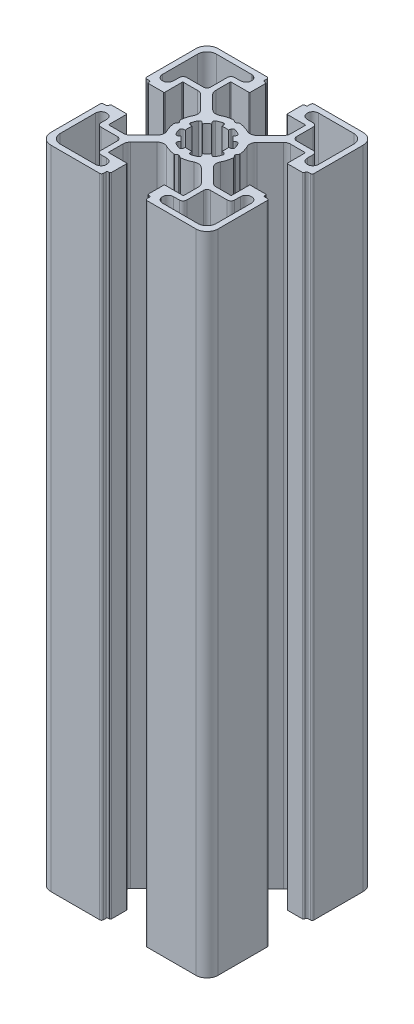
SolidWorks part; units mm, degrees
ref_plane "Front Plane" through (0, 0, 0) normal (0, 0, 1) x (1, 0, 0)
ref_plane "Top Plane" through (0, 0, 0) normal (0, 1, 0) x (1, 0, 0)
ref_plane "Right Plane" through (0, 0, 0) normal (1, 0, 0) x (0, 0, -1)
sketch "Sketch1" plane through (0, 0, 0) normal (0, 1, 0) x (1, 0, 0)
  line L106 (-18, 9.0002) -> (-18, 10.55)
  line L107 (-21, 18.5) -> (-21, 9.0002)
  line L108 (-9, 21) -> (-18.5, 21)
  line L109 (-10.55, 18) -> (-9, 18)
  line L110 (0.9675, 5.4811) -> (0.8674, 4.9242)
  line L111 (2.864, 4.0985) -> (3.1913, 4.5626)
  line L112 (4.5668, 3.2081) -> (4.0897, 2.8765)
  line L113 (4.9205, 0.8878) -> (5.4897, 0.9862)
  line L114 (5.4898, -0.9862) -> (4.9205, -0.8878)
  line L115 (4.0897, -2.8765) -> (4.5668, -3.2082)
  line L116 (3.1914, -4.5627) -> (2.864, -4.0985)
  line L117 (0.8674, -4.9242) -> (0.9675, -5.4811)
  line L118 (-0.9675, -5.4811) -> (-0.8674, -4.9242)
  line L119 (-2.864, -4.0985) -> (-3.1913, -4.5626)
  line L120 (-4.5668, -3.2082) -> (-4.0897, -2.8765)
  line L121 (-4.9205, -0.8878) -> (-5.4897, -0.9862)
  line L122 (-5.4899, 0.9862) -> (-4.9205, 0.8878)
  line L123 (-4.0897, 2.8765) -> (-4.5668, 3.2081)
  line L124 (-3.1914, 4.5627) -> (-2.864, 4.0985)
  line L125 (-0.8674, 4.9242) -> (-0.9675, 5.4811)
  line L126 (-11.55, 12.55) -> (-11.55, 17)
  line L127 (-17, 11.55) -> (-12.55, 11.55)
  line L128 (-21, -9.0002) -> (-21, -18.5)
  line L129 (-18, -10.55) -> (-18, -9.0002)
  line L130 (-12.55, -11.55) -> (-17, -11.55)
  line L131 (-11.55, -17) -> (-11.55, -12.55)
  line L132 (-9, -18) -> (-10.55, -18)
  line L133 (-18.5, -21) -> (-9, -21)
  line L134 (21, 9.0002) -> (21, 18.5)
  line L135 (18, 10.55) -> (18, 9.0002)
  line L136 (12.55, 11.55) -> (17, 11.55)
  line L137 (11.55, 17) -> (11.55, 12.55)
  line L138 (9, 18) -> (10.55, 18)
  line L139 (18.5, 21) -> (9, 21)
  line L140 (17, -11.55) -> (12.55, -11.55)
  line L141 (18, -9.0002) -> (18, -10.55)
  line L142 (21, -18.5) -> (21, -9.0002)
  line L143 (9, -21) -> (18.5, -21)
  line L144 (10.55, -18) -> (9, -18)
  line L145 (11.55, -12.55) -> (11.55, -17)
  line L146 (7.5635, 5.8587) -> (11.1298, 9.425)
  line L147 (12.5048, 9.9945) -> (16.3169, 9.9945)
  line L148 (16.5169, 9.7945) -> (16.5169, 5.2)
  line L149 (16.7169, 5) -> (20.7196, 5)
  line L150 (21.0196, 5.3) -> (21.0196, 5.5)
  line L151 (21.3196, 5.8) -> (22, 5.8)
  line L152 (22.5, 6.3) -> (22.5, 19.5)
  line L153 (19.5, 22.5) -> (6.3757, 22.5)
  line L154 (5.8757, 22) -> (5.8757, 21.3)
  line L155 (5.5757, 21) -> (5.3, 21)
  line L156 (5, 20.7) -> (5, 16.6668)
  line L157 (5.2, 16.4668) -> (9.9054, 16.4668)
  line L158 (10.1054, 16.2668) -> (10.1054, 12.4716)
  line L159 (9.5196, 11.0574) -> (5.9449, 7.4827)
  line L160 (0.7548, 7.9748) -> (0.1126, 7.6069)
  line L161 (-0.1126, 7.6069) -> (-0.7547, 7.9748)
  line L162 (-5.9449, 7.4827) -> (-9.5196, 11.0574)
  line L163 (-10.1054, 12.4716) -> (-10.1054, 16.2668)
  line L164 (-9.9054, 16.4668) -> (-5.2, 16.4668)
  line L165 (-5, 16.6668) -> (-5, 20.7)
  line L166 (-5.3, 21) -> (-5.5757, 21)
  line L167 (-5.8757, 21.3) -> (-5.8757, 22)
  line L168 (-6.3757, 22.5) -> (-19.5, 22.5)
  line L169 (-22.5, 19.5) -> (-22.5, 6.3)
  line L170 (-22, 5.8) -> (-21.3196, 5.8)
  line L171 (-21.0196, 5.5) -> (-21.0196, 5.3)
  line L172 (-20.7196, 5) -> (-16.7169, 5)
  line L173 (-16.5169, 5.2) -> (-16.5169, 9.7945)
  line L174 (-16.3169, 9.9945) -> (-12.5048, 9.9945)
  line L175 (-11.1298, 9.425) -> (-7.5635, 5.8587)
  line L176 (-7.974, 0.7926) -> (-7.5401, 0.0468)
  line L177 (-7.5401, -0.0468) -> (-7.974, -0.7926)
  line L178 (-7.5635, -5.8587) -> (-11.1298, -9.425)
  line L179 (-12.5048, -9.9945) -> (-16.3169, -9.9945)
  line L180 (-16.5169, -9.7945) -> (-16.5169, -5.2)
  line L181 (-16.7169, -5) -> (-20.7196, -5)
  line L182 (-21.0196, -5.3) -> (-21.0196, -5.5)
  line L183 (-21.3196, -5.8) -> (-22, -5.8)
  line L184 (-22.5, -6.3) -> (-22.5, -19.5)
  line L185 (-19.5, -22.5) -> (-6.3757, -22.5)
  line L186 (-5.8757, -22) -> (-5.8757, -21.3)
  line L187 (-5.5757, -21) -> (-5.3, -21)
  line L188 (-5, -20.7) -> (-5, -16.6668)
  line L189 (-5.2, -16.4668) -> (-9.9054, -16.4668)
  line L190 (-10.1054, -16.2668) -> (-10.1054, -12.4716)
  line L191 (-9.5196, -11.0574) -> (-5.9449, -7.4827)
  line L192 (-0.7547, -7.9748) -> (-0.1126, -7.6069)
  line L193 (0.1126, -7.6069) -> (0.7548, -7.9748)
  line L194 (5.9449, -7.4827) -> (9.5196, -11.0574)
  line L195 (10.1054, -12.4716) -> (10.1054, -16.2668)
  line L196 (9.9054, -16.4668) -> (5.2, -16.4668)
  line L197 (5, -16.6668) -> (5, -20.7)
  line L198 (5.3, -21) -> (5.5757, -21)
  line L199 (5.8757, -21.3) -> (5.8757, -22)
  line L200 (6.3757, -22.5) -> (19.5, -22.5)
  line L201 (22.5, -19.5) -> (22.5, -6.3)
  line L202 (22, -5.8) -> (21.3196, -5.8)
  line L203 (21.0196, -5.5) -> (21.0196, -5.3)
  line L204 (20.7196, -5) -> (16.7169, -5)
  line L205 (16.5169, -5.2) -> (16.5169, -9.7945)
  line L206 (16.3169, -9.9945) -> (12.5048, -9.9945)
  line L207 (11.1298, -9.425) -> (7.5635, -5.8587)
  line L208 (7.974, -0.7926) -> (7.5401, -0.0468)
  line L209 (7.5401, 0.0468) -> (7.974, 0.7926)
  arc A140 (-17, 11.55) -> (-18, 10.55) centre (-17, 10.55) ccw
  arc A141 (-21, 9.0002) -> (-18, 9.0002) centre (-19.5, 9.0002) ccw
  arc A142 (-18.5, 21) -> (-21, 18.5) centre (-18.5, 18.5) ccw
  arc A143 (-9, 18) -> (-9, 21) centre (-9, 19.5) ccw
  arc A144 (-10.55, 18) -> (-11.55, 17) centre (-10.55, 17) ccw
  arc A145 (-12.55, 11.55) -> (-11.55, 12.55) centre (-12.55, 12.55) ccw
  arc A146 (-21, -18.5) -> (-18.5, -21) centre (-18.5, -18.5) ccw
  arc A147 (-18, -9.0002) -> (-21, -9.0002) centre (-19.5, -9.0002) ccw
  arc A148 (-18, -10.55) -> (-17, -11.55) centre (-17, -10.55) ccw
  arc A149 (-11.55, -12.55) -> (-12.55, -11.55) centre (-12.55, -12.55) ccw
  arc A150 (-11.55, -17) -> (-10.55, -18) centre (-10.55, -17) ccw
  arc A151 (-9, -21) -> (-9, -18) centre (-9, -19.5) ccw
  arc A152 (0.8674, 4.9242) -> (-0.8674, 4.9242) centre (0, 0) ccw
  arc A153 (1.5951, 5.8941) -> (0.9675, 5.4811) centre (1.4627, 5.4119) ccw
  arc A154 (3.0417, 5.301) -> (1.5951, 5.8941) centre (0.0235, 0) ccw
  arc A155 (3.1913, 4.5626) -> (3.0417, 5.301) centre (2.7943, 4.8665) ccw
  arc A156 (4.0897, 2.8765) -> (2.864, 4.0985) centre (0, 0) ccw
  arc A157 (5.3025, 3.0565) -> (4.5668, 3.2081) centre (4.868, 2.8091) ccw
  arc A158 (5.906, 1.6142) -> (5.3025, 3.0565) centre (0.0235, 0) ccw
  arc A159 (5.4897, 0.9862) -> (5.906, 1.6142) centre (5.4239, 1.4819) ccw
  arc A160 (4.9205, -0.8878) -> (4.9205, 0.8878) centre (0, 0) ccw
  arc A161 (5.906, -1.6142) -> (5.4898, -0.9862) centre (5.4239, -1.4819) ccw
  arc A162 (5.3025, -3.0564) -> (5.906, -1.6142) centre (0.0235, 0) ccw
  arc A163 (4.5668, -3.2082) -> (5.3025, -3.0564) centre (4.868, -2.8091) ccw
  arc A164 (2.864, -4.0985) -> (4.0897, -2.8765) centre (0, 0) ccw
  arc A165 (3.0416, -5.301) -> (3.1914, -4.5627) centre (2.7943, -4.8665) ccw
  arc A166 (1.5951, -5.8941) -> (3.0416, -5.301) centre (0.0235, 0) ccw
  arc A167 (0.9675, -5.4811) -> (1.5951, -5.8941) centre (1.4627, -5.4119) ccw
  arc A168 (-0.8674, -4.9242) -> (0.8674, -4.9242) centre (0, 0) ccw
  arc A169 (-1.5951, -5.8941) -> (-0.9675, -5.4811) centre (-1.4627, -5.4119) ccw
  arc A170 (-3.0416, -5.301) -> (-1.5951, -5.8941) centre (-0.0235, 0) ccw
  arc A171 (-3.1913, -4.5626) -> (-3.0416, -5.301) centre (-2.7943, -4.8665) ccw
  arc A172 (-4.0897, -2.8765) -> (-2.864, -4.0985) centre (0, 0) ccw
  arc A173 (-5.3025, -3.0565) -> (-4.5668, -3.2082) centre (-4.868, -2.8091) ccw
  arc A174 (-5.906, -1.6142) -> (-5.3025, -3.0565) centre (-0.0235, 0) ccw
  arc A175 (-5.4897, -0.9862) -> (-5.906, -1.6142) centre (-5.4239, -1.4819) ccw
  arc A176 (-4.9205, 0.8878) -> (-4.9205, -0.8878) centre (0, 0) ccw
  arc A177 (-5.906, 1.6141) -> (-5.4899, 0.9862) centre (-5.4239, 1.4818) ccw
  arc A178 (-5.3025, 3.0564) -> (-5.906, 1.6141) centre (-0.0235, 0) ccw
  arc A179 (-4.5668, 3.2081) -> (-5.3025, 3.0564) centre (-4.868, 2.8091) ccw
  arc A180 (-2.864, 4.0985) -> (-4.0897, 2.8765) centre (0, 0) ccw
  arc A181 (-3.0417, 5.301) -> (-3.1914, 4.5627) centre (-2.7943, 4.8665) ccw
  arc A182 (-1.5951, 5.8941) -> (-3.0417, 5.301) centre (-0.0235, 0) ccw
  arc A183 (-0.9675, 5.4811) -> (-1.5951, 5.8941) centre (-1.4627, 5.4119) ccw
  arc A184 (21, 18.5) -> (18.5, 21) centre (18.5, 18.5) ccw
  arc A185 (18, 9.0002) -> (21, 9.0002) centre (19.5, 9.0002) ccw
  arc A186 (18, 10.55) -> (17, 11.55) centre (17, 10.55) ccw
  arc A187 (11.55, 12.55) -> (12.55, 11.55) centre (12.55, 12.55) ccw
  arc A188 (11.55, 17) -> (10.55, 18) centre (10.55, 17) ccw
  arc A189 (9, 21) -> (9, 18) centre (9, 19.5) ccw
  arc A190 (12.55, -11.55) -> (11.55, -12.55) centre (12.55, -12.55) ccw
  arc A191 (17, -11.55) -> (18, -10.55) centre (17, -10.55) ccw
  arc A192 (21, -9.0002) -> (18, -9.0002) centre (19.5, -9.0002) ccw
  arc A193 (18.5, -21) -> (21, -18.5) centre (18.5, -18.5) ccw
  arc A194 (9, -18) -> (9, -21) centre (9, -19.5) ccw
  arc A195 (10.55, -18) -> (11.55, -17) centre (10.55, -17) ccw
  arc A196 (7.9999, 0.9154) -> (7.2004, 3.6119) centre (0.0496, 0.0249) ccw
  arc A197 (7.5635, 5.8587) -> (7.2004, 3.6119) centre (8.9385, 4.4837) ccw
  arc A198 (12.5048, 9.9945) -> (11.1298, 9.425) centre (12.5048, 8.05) ccw
  arc A199 (16.5169, 9.7945) -> (16.3169, 9.9945) centre (16.3169, 9.7945) ccw
  arc A200 (16.5169, 5.2) -> (16.7169, 5) centre (16.7169, 5.2) ccw
  arc A201 (20.7196, 5) -> (21.0196, 5.3) centre (20.7196, 5.3) ccw
  arc A202 (21.3196, 5.8) -> (21.0196, 5.5) centre (21.3196, 5.5) ccw
  arc A203 (22, 5.8) -> (22.5, 6.3) centre (22, 6.3) ccw
  arc A204 (22.5, 19.5) -> (19.5, 22.5) centre (19.5, 19.5) ccw
  arc A205 (6.3757, 22.5) -> (5.8757, 22) centre (6.3757, 22) ccw
  arc A206 (5.5757, 21) -> (5.8757, 21.3) centre (5.5757, 21.3) ccw
  arc A207 (5.3, 21) -> (5, 20.7) centre (5.3, 20.7) ccw
  arc A208 (5, 16.6668) -> (5.2, 16.4668) centre (5.2, 16.6668) ccw
  arc A209 (10.1054, 16.2668) -> (9.9054, 16.4668) centre (9.9054, 16.2668) ccw
  arc A210 (9.5196, 11.0574) -> (10.1054, 12.4716) centre (8.1054, 12.4716) ccw
  arc A211 (3.6665, 7.1733) -> (5.9449, 7.4827) centre (4.5855, 8.9496) ccw
  arc A212 (3.6665, 7.1733) -> (0.8753, 8.0001) centre (0.0235, 0) ccw
  arc A213 (0.8753, 8.0001) -> (0.7548, 7.9748) centre (0.8542, 7.8013) ccw
  arc A214 (0, 7.531) -> (0.1126, 7.6069) centre (-0.0489, 7.7249) ccw
  arc A215 (-0.1126, 7.6069) -> (0, 7.531) centre (0.0489, 7.7249) ccw
  arc A216 (-0.7547, 7.9748) -> (-0.8753, 8.0001) centre (-0.8542, 7.8013) ccw
  arc A217 (-0.8753, 8.0001) -> (-3.6665, 7.1733) centre (-0.0235, 0) ccw
  arc A218 (-5.9449, 7.4827) -> (-3.6665, 7.1733) centre (-4.5855, 8.9496) ccw
  arc A219 (-10.1054, 12.4716) -> (-9.5196, 11.0574) centre (-8.1054, 12.4716) ccw
  arc A220 (-9.9054, 16.4668) -> (-10.1054, 16.2668) centre (-9.9054, 16.2668) ccw
  arc A221 (-5.2, 16.4668) -> (-5, 16.6668) centre (-5.2, 16.6668) ccw
  arc A222 (-5, 20.7) -> (-5.3, 21) centre (-5.3, 20.7) ccw
  arc A223 (-5.8757, 21.3) -> (-5.5757, 21) centre (-5.5757, 21.3) ccw
  arc A224 (-5.8757, 22) -> (-6.3757, 22.5) centre (-6.3757, 22) ccw
  arc A225 (-19.5, 22.5) -> (-22.5, 19.5) centre (-19.5, 19.5) ccw
  arc A226 (-22.5, 6.3) -> (-22, 5.8) centre (-22, 6.3) ccw
  arc A227 (-21.0196, 5.5) -> (-21.3196, 5.8) centre (-21.3196, 5.5) ccw
  arc A228 (-21.0196, 5.3) -> (-20.7196, 5) centre (-20.7196, 5.3) ccw
  arc A229 (-16.7169, 5) -> (-16.5169, 5.2) centre (-16.7169, 5.2) ccw
  arc A230 (-16.3169, 9.9945) -> (-16.5169, 9.7945) centre (-16.3169, 9.7945) ccw
  arc A231 (-11.1298, 9.425) -> (-12.5048, 9.9945) centre (-12.5048, 8.05) ccw
  arc A232 (-7.2004, 3.6119) -> (-7.5635, 5.8587) centre (-8.9385, 4.4837) ccw
  arc A233 (-7.2004, 3.6119) -> (-7.9999, 0.9154) centre (-0.0496, 0.0249) ccw
  arc A234 (-7.9999, 0.9154) -> (-7.974, 0.7926) centre (-7.8011, 0.8932) ccw
  arc A235 (-7.5313, 0) -> (-7.5401, 0.0468) centre (-7.7309, -0.013) ccw
  arc A236 (-7.5401, -0.0468) -> (-7.5313, 0) centre (-7.7309, 0.013) ccw
  arc A237 (-7.974, -0.7926) -> (-7.9999, -0.9154) centre (-7.8011, -0.8932) ccw
  arc A238 (-7.9999, -0.9154) -> (-7.2004, -3.6119) centre (-0.0496, -0.0249) ccw
  arc A239 (-7.5635, -5.8587) -> (-7.2004, -3.6119) centre (-8.9385, -4.4837) ccw
  arc A240 (-12.5048, -9.9945) -> (-11.1298, -9.425) centre (-12.5048, -8.05) ccw
  arc A241 (-16.5169, -9.7945) -> (-16.3169, -9.9945) centre (-16.3169, -9.7945) ccw
  arc A242 (-16.5169, -5.2) -> (-16.7169, -5) centre (-16.7169, -5.2) ccw
  arc A243 (-20.7196, -5) -> (-21.0196, -5.3) centre (-20.7196, -5.3) ccw
  arc A244 (-21.3196, -5.8) -> (-21.0196, -5.5) centre (-21.3196, -5.5) ccw
  arc A245 (-22, -5.8) -> (-22.5, -6.3) centre (-22, -6.3) ccw
  arc A246 (-22.5, -19.5) -> (-19.5, -22.5) centre (-19.5, -19.5) ccw
  arc A247 (-6.3757, -22.5) -> (-5.8757, -22) centre (-6.3757, -22) ccw
  arc A248 (-5.5757, -21) -> (-5.8757, -21.3) centre (-5.5757, -21.3) ccw
  arc A249 (-5.3, -21) -> (-5, -20.7) centre (-5.3, -20.7) ccw
  arc A250 (-5, -16.6668) -> (-5.2, -16.4668) centre (-5.2, -16.6668) ccw
  arc A251 (-10.1054, -16.2668) -> (-9.9054, -16.4668) centre (-9.9054, -16.2668) ccw
  arc A252 (-9.5196, -11.0574) -> (-10.1054, -12.4716) centre (-8.1054, -12.4716) ccw
  arc A253 (-3.6665, -7.1733) -> (-5.9449, -7.4827) centre (-4.5855, -8.9496) ccw
  arc A254 (-3.6665, -7.1733) -> (-0.8753, -8.0001) centre (-0.0235, 0) ccw
  arc A255 (-0.8753, -8.0001) -> (-0.7547, -7.9748) centre (-0.8542, -7.8013) ccw
  arc A256 (0, -7.531) -> (-0.1126, -7.6069) centre (0.0489, -7.7249) ccw
  arc A257 (0.1126, -7.6069) -> (0, -7.531) centre (-0.0489, -7.7249) ccw
  arc A258 (0.7548, -7.9748) -> (0.8753, -8.0001) centre (0.8542, -7.8012) ccw
  arc A259 (0.8753, -8.0001) -> (3.6665, -7.1733) centre (0.0235, 0) ccw
  arc A260 (5.9449, -7.4827) -> (3.6665, -7.1733) centre (4.5855, -8.9496) ccw
  arc A261 (10.1054, -12.4716) -> (9.5196, -11.0574) centre (8.1054, -12.4716) ccw
  arc A262 (9.9054, -16.4668) -> (10.1054, -16.2668) centre (9.9054, -16.2668) ccw
  arc A263 (5.2, -16.4668) -> (5, -16.6668) centre (5.2, -16.6668) ccw
  arc A264 (5, -20.7) -> (5.3, -21) centre (5.3, -20.7) ccw
  arc A265 (5.8757, -21.3) -> (5.5757, -21) centre (5.5757, -21.3) ccw
  arc A266 (5.8757, -22) -> (6.3757, -22.5) centre (6.3757, -22) ccw
  arc A267 (19.5, -22.5) -> (22.5, -19.5) centre (19.5, -19.5) ccw
  arc A268 (22.5, -6.3) -> (22, -5.8) centre (22, -6.3) ccw
  arc A269 (21.0196, -5.5) -> (21.3196, -5.8) centre (21.3196, -5.5) ccw
  arc A270 (21.0196, -5.3) -> (20.7196, -5) centre (20.7196, -5.3) ccw
  arc A271 (16.7169, -5) -> (16.5169, -5.2) centre (16.7169, -5.2) ccw
  arc A272 (16.3169, -9.9945) -> (16.5169, -9.7945) centre (16.3169, -9.7945) ccw
  arc A273 (11.1298, -9.425) -> (12.5048, -9.9945) centre (12.5048, -8.05) ccw
  arc A274 (7.2004, -3.6119) -> (7.5635, -5.8587) centre (8.9385, -4.4837) ccw
  arc A275 (7.2004, -3.6119) -> (7.9999, -0.9154) centre (0.0496, -0.0249) ccw
  arc A276 (7.9999, -0.9154) -> (7.974, -0.7926) centre (7.8011, -0.8932) ccw
  arc A277 (7.5313, 0) -> (7.5401, -0.0468) centre (7.7309, 0.013) ccw
  arc A278 (7.5401, 0.0468) -> (7.5313, 0) centre (7.7309, -0.013) ccw
  arc A279 (7.974, 0.7926) -> (7.9999, 0.9154) centre (7.8011, 0.8932) ccw
extrude "Boss-Extrude1" add sketch "Sketch1" along normal blind 174
